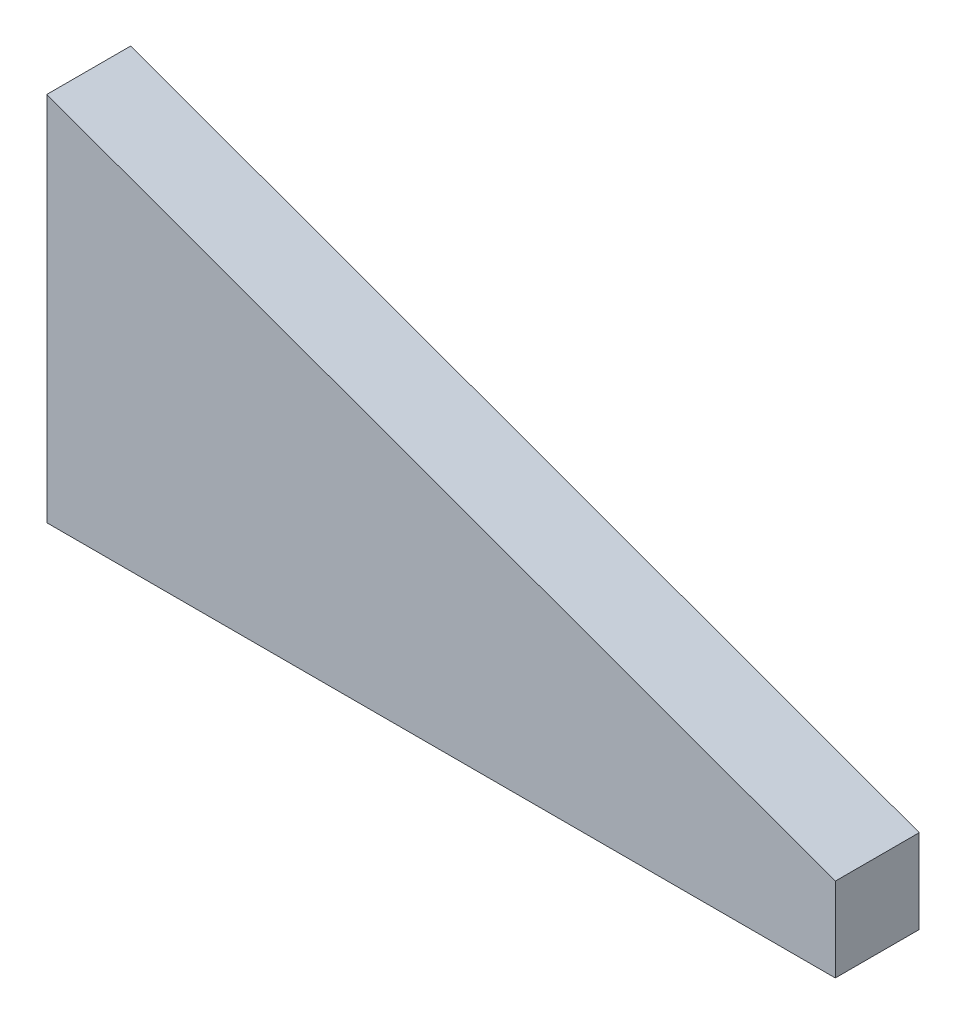
SolidWorks part; units mm, degrees
ref_plane "Plan de face" through (0, 0, 0) normal (0, 0, 1) x (1, 0, 0)
ref_plane "Plan de dessus" through (0, 0, 0) normal (0, 1, 0) x (1, 0, 0)
ref_plane "Plan de droite" through (0, 0, 0) normal (1, 0, 0) x (0, 0, -1)
sketch "Esquisse1" plane through (0, 0, 0) normal (0, 0, 1) x (1, 0, 0)
  line L1 (-54.3611, -21.0299) -> (-101.3457, -3.9289)
  line L2 (-101.3457, -3.9289) -> (-101.3457, -21.0299)
  line L3 (-101.3457, -21.0299) -> (-101.3457, -26.0299)
  line L4 (-101.3457, -26.0299) -> (-54.3611, -26.0299)
  line L5 (-54.3611, -26.0299) -> (-54.3611, -21.0299)
  dimension "D2" = 50
  dimension "D3" = 5
extrude "Boss.-Extru.1" add sketch "Esquisse1" along normal blind 5
